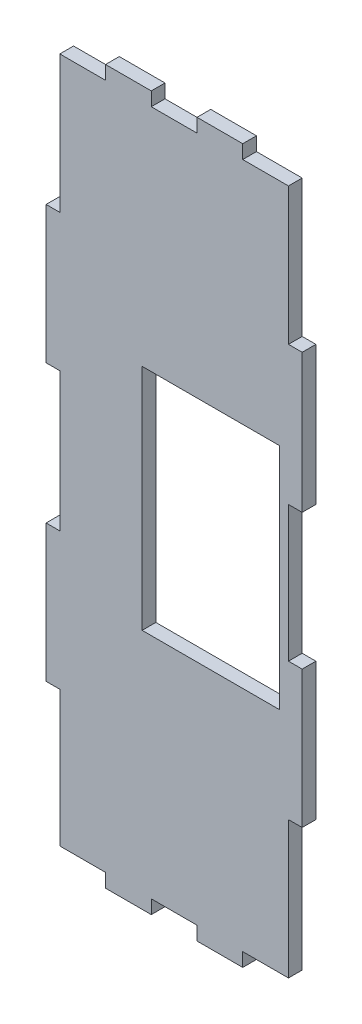
SolidWorks part; units mm, degrees
material "Pinho"
ref_plane "Plano frontal" through (0, 0, 0) normal (0, 0, 1) x (1, 0, 0)
ref_plane "Plano superior" through (0, 0, 0) normal (0, 1, 0) x (1, 0, 0)
ref_plane "Plano direito" through (0, 0, 0) normal (1, 0, 0) x (0, 0, -1)
sketch "Esboço1" plane through (0, 0, 0) normal (0, 0, 1) x (1, 0, 0)
  line L0 (-0.6175, -25.4829) -> (-0.6175, -55.8057)
  line L2 (-0.6175, 34.5171) -> (-0.6175, 4.5171)
  line L5 (-0.6175, -85.8057) -> (-0.6175, -115.4829)
  line L6 (-0.6175, -25.4829) -> (-3.6175, -25.4829)
  line L9 (-0.6175, 4.5171) -> (-3.6175, 4.5171)
  line L10 (-3.6175, -25.4829) -> (-3.6175, 4.5171)
  line L13 (-3.6175, -85.8057) -> (-0.6175, -85.8057)
  line L14 (-3.6175, -85.8057) -> (-3.6175, -55.8057)
  line L15 (-3.6175, -55.8057) -> (-0.6175, -55.8057)
  line L27 (49.3825, -85.4829) -> (49.3825, -115.4829)
  line L34 (49.3825, -85.4829) -> (52.3825, -85.4829)
  line L36 (49.3825, -55.4829) -> (52.3825, -55.4829)
  line L37 (52.3825, -85.4829) -> (52.3825, -55.4829)
  line L50 (49.3825, 34.5171) -> (49.3825, 4.5171)
  line L51 (49.3825, 4.5171) -> (52.3825, 4.5171)
  line L56 (52.3825, 4.5171) -> (52.3825, -25.8057)
  line L57 (52.3825, -25.8057) -> (49.3825, -25.8057)
  line L62 (49.3825, -25.8057) -> (49.3825, -55.4829)
  line L69 (9.3825, -118.4829) -> (9.3825, -115.4829)
  line L78 (19.3825, -115.4829) -> (19.3825, -118.4829)
  line L80 (29.3825, -118.4829) -> (29.3825, -115.4829)
  line L82 (39.3825, -115.4829) -> (39.3825, -118.4829)
  line L85 (9.3825, 37.5171) -> (9.3825, 34.5171)
  line L87 (19.3825, 34.5171) -> (19.3825, 37.5171)
  line L89 (29.3825, 37.5171) -> (29.3825, 34.5171)
  line L91 (39.3825, 34.5171) -> (39.3825, 37.5171)
  line L93 (17.3825, -15.6443) -> (17.3825, -115.4829) construction
  line L94 (-0.6175, -40.6443) -> (49.3825, -40.6443) construction
  line L95 (9.3825, 37.5171) -> (19.3825, 37.5171)
  line L96 (17.3825, -15.6443) -> (47.3825, -15.6443)
  line L97 (17.3825, -15.6443) -> (17.3825, -65.6443)
  line L98 (17.3825, -65.6443) -> (47.3825, -65.6443)
  line L99 (47.3825, -15.6443) -> (47.3825, -65.6443)
  line L100 (17.3825, -15.6443) -> (47.3825, -65.6443) construction
  line L101 (17.3825, -65.6443) -> (47.3825, -15.6443) construction
  line L102 (29.3825, 37.5171) -> (39.3825, 37.5171)
  line L103 (-0.6175, 34.5171) -> (9.3825, 34.5171)
  line L104 (49.3825, 34.5171) -> (39.3825, 34.5171)
  line L105 (19.3825, 34.5171) -> (29.3825, 34.5171)
  line L106 (-0.6175, -115.4829) -> (9.3825, -115.4829)
  line L107 (19.3825, -115.4829) -> (29.3825, -115.4829)
  line L108 (39.3825, -115.4829) -> (49.3825, -115.4829)
  line L109 (9.3825, -118.4829) -> (19.3825, -118.4829)
  line L110 (29.3825, -118.4829) -> (39.3825, -118.4829)
  point P0 (0, 0)
  point P46 (32.3825, -40.6443)
  dimension "D1" = 150
  dimension "D2" = 50
  dimension "D3" = 30
  dimension "D4" = 30
  dimension "D6" = 10
  dimension "D7" = 50
  dimension "D8" = 30
  dimension "D9" = 17
  dimension "D10" = 30
  dimension "D11" = 3
  dimension "D13" = 30
  dimension "D21" = 3
  dimension "D28" = 3
  dimension "D29" = 3
extrude "Ressalto-extrusão1" add sketch "Esboço1" along normal blind 3
